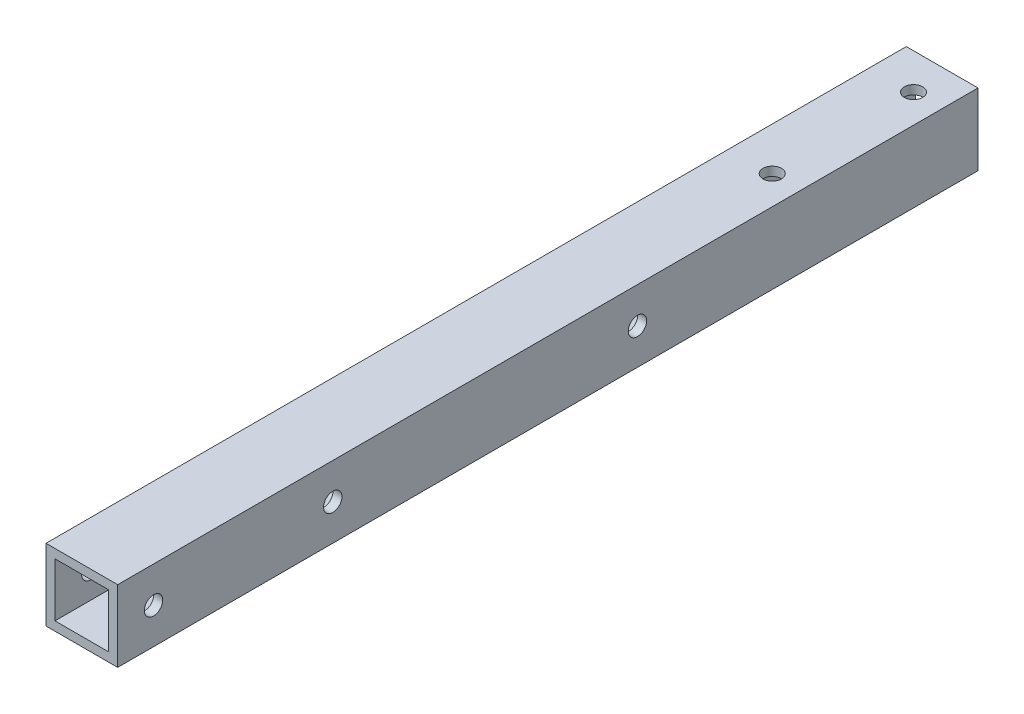
SolidWorks part; units mm, degrees
material "1060 Alloy"
ref_plane "Front Plane" through (0, 0, 0) normal (0, 0, 1) x (1, 0, 0)
ref_plane "Top Plane" through (0, 0, 0) normal (0, 1, 0) x (1, 0, 0)
ref_plane "Right Plane" through (0, 0, 0) normal (1, 0, 0) x (0, 0, -1)
sketch "Sketch2" plane through (0, 0, 0) normal (0, 0, 1) x (1, 0, 0)
  line L1 (12.7, -12.7) -> (-12.7, -12.7)
  line L2 (12.7, -12.7) -> (12.7, 12.7)
  line L3 (12.7, 12.7) -> (-12.7, 12.7)
  line L4 (-12.7, -12.7) -> (-12.7, 12.7)
  line L5 (12.7, -12.7) -> (-12.7, 12.7) construction
  line L6 (12.7, 12.7) -> (-12.7, -12.7) construction
  point P0 (0, 0)
extrude "Boss-Extrude1" add sketch "Sketch2" along normal blind 304.8 contours L4 L3 L2 L1
sketch "Sketch4" plane through (0, 0, 0) normal (0, 0, 1) x (1, 0, 0)
  line L0 (12.7, -12.7) -> (12.7, 12.7) construction
  line L1 (-9.525, -9.525) -> (9.525, -9.525)
  line L2 (-9.525, -9.525) -> (-9.525, 9.525)
  line L3 (-9.525, 9.525) -> (9.525, 9.525)
  line L4 (9.525, -9.525) -> (9.525, 9.525)
  line L5 (-9.525, -9.525) -> (9.525, 9.525) construction
  line L6 (-9.525, 9.525) -> (9.525, -9.525) construction
  line L7 (12.7, 12.7) -> (-12.7, 12.7) construction
  point P0 (0, 0)
  dimension "D1" = 3.175
  dimension "D2" = 3.175
extrude "Cut-Extrude1" cut sketch "Sketch4" along normal through all
sketch "Sketch5" plane through (0, 12.7, 0) normal (0, 1, 0) x (1, 0, 0)
  line L0 (12.7, 0) -> (-12.7, 0) construction
  line L1 (-12.7, -304.8) -> (-12.7, 0) construction
  circle A0 centre (2.54, -12.7) radius 3.2639
  dimension "D1" = 12.7
  dimension "D2" = 15.24
extrude "Cut-Extrude2" cut sketch "Sketch5" against normal blind 304.8 contours A0
sketch "Sketch6" plane through (0, 12.7, 0) normal (0, 1, 0) x (1, 0, 0)
  line L0 (-12.7, -304.8) -> (-12.7, 0) construction
  line L1 (-9.525, -304.8) -> (-9.525, 0) construction
  circle A0 centre (2.54, -62.738) radius 3.2639
  circle A1 centre (2.54, -12.7) radius 3.2639 construction
  dimension "D1" = 3.175
  dimension "D2" = 50.038
extrude "Cut-Extrude3" cut sketch "Sketch6" against normal blind 304.8
sketch "Sketch7" plane through (0, 12.7, 0) normal (0, 1, 0) x (1, 0, 0)
  line L0 (-12.7, -304.8) -> (-12.7, 0) construction
  line L1 (12.7, -304.8) -> (-12.7, -304.8) construction
  circle A0 centre (0, -292.1) radius 3.2639
  dimension "D1" = 6.5278
  dimension "D2" = 12.7
  dimension "D3" = 12.7
sketch "Sketch8" plane through (-12.7, 0, 0) normal (-1, 0, 0) x (0, 0, 1)
  line L0 (304.8, -12.7) -> (304.8, 12.7) construction
  line L1 (304.8, -12.7) -> (0, -12.7) construction
  circle A0 centre (292.1, 0) radius 3.2639
  dimension "D1" = 6.5278
  dimension "D2" = 12.7
  dimension "D3" = 12.7
extrude "Cut-Extrude5" cut sketch "Sketch8" against normal through all
sketch "Sketch9" plane through (12.7, 0, 0) normal (1, 0, 0) x (0, 0, -1)
  line L0 (-304.8, -12.7) -> (-304.8, 12.7) construction
  line L1 (-304.8, -12.7) -> (0, -12.7) construction
  circle A0 centre (-228.6, 0) radius 3.2639
  dimension "D3" = 6.5278
  dimension "D1" = 76.2
  dimension "D2" = 12.7
extrude "Cut-Extrude6" cut sketch "Sketch9" against normal through all
sketch "Sketch10" plane through (-12.7, 0, 0) normal (-1, 0, 0) x (0, 0, 1)
  line L0 (304.8, -12.7) -> (0, -12.7) construction
  line L1 (0, -12.7) -> (0, 12.7) construction
  circle A0 centre (120.65, 0) radius 3.2639
  dimension "D3" = 6.5278
  dimension "D1" = 12.7
  dimension "D2" = 120.65
extrude "Cut-Extrude7" cut sketch "Sketch10" against normal through all
